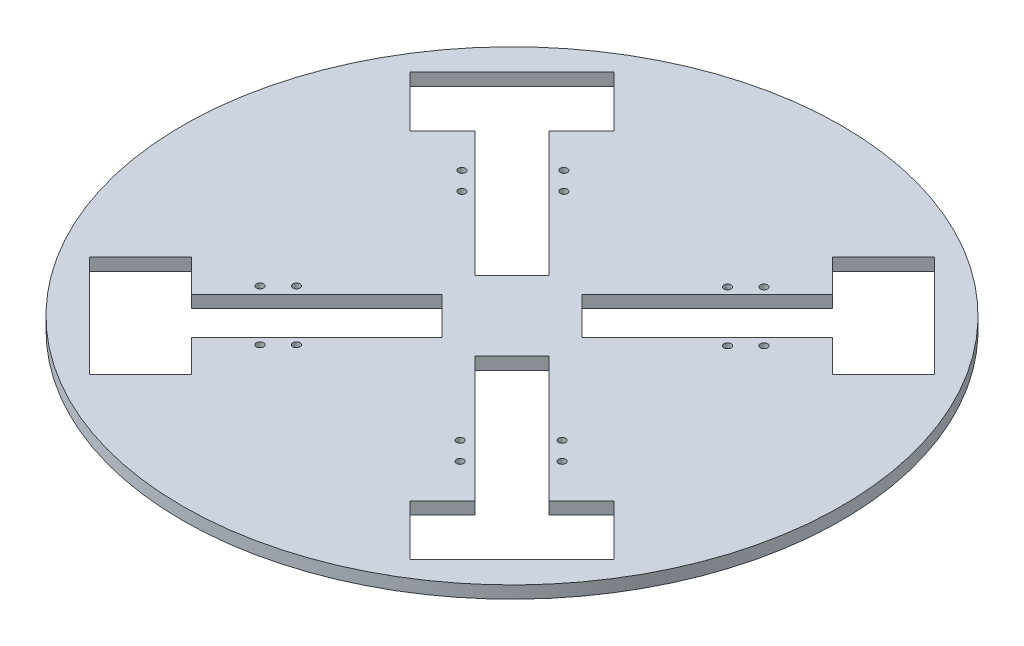
SolidWorks part; units mm, degrees
ref_plane "Front Plane" through (0, 0, 0) normal (0, 0, 1) x (1, 0, 0)
ref_plane "Top Plane" through (0, 0, 0) normal (0, 1, 0) x (1, 0, 0)
ref_plane "Right Plane" through (0, 0, 0) normal (1, 0, 0) x (0, 0, -1)
sketch "Sketch1" plane through (0, 0, 0) normal (0, 1, 0) x (1, 0, 0)
  line L1 (0, 0) -> (-200, 0) construction
  line L2 (0, 0) -> (0, 200) construction
  line L3 (0, 200) -> (-200, 200) construction
  line L4 (-200, 0) -> (-200, 200) construction
  circle A0 centre (-100, 100) radius 160
  point P8 (-100, 200)
  point P9 (-200, 100)
  dimension "D3" = 320
  dimension "D1" = 200
  dimension "D2" = 200
extrude "Boss-Extrude1" add sketch "Sketch1" along normal blind 6 contours A0
sketch "Sketch2" plane through (0, 6, 0) normal (0, 1, 0) x (1, 0, 0)
  line L0 (-260, 100) -> (60, 100) construction
  line L1 (-213.1371, -13.1371) -> (-100, 100) construction
  line L2 (-100, 100) -> (13.1371, 213.1371) construction
  line L3 (-213.1371, 213.1371) -> (13.1371, -13.1371) construction
  circle A0 centre (-100, 100) radius 160 construction
  dimension "D1" = 45
  dimension "D2" = 45
sketch "Sketch3" plane through (0, 0, 0) normal (0, -1, 0) x (1, 0, 0)
  line L0 (-22.2183, -227.2792) -> (-46.967, -202.5305)
  line L1 (-22.2183, -227.2792) -> (27.2792, -177.7817)
  line L2 (-46.967, -202.5305) -> (2.5305, -153.033)
  line L3 (27.2792, -177.7817) -> (2.5305, -153.033)
  line L4 (2.5305, -46.967) -> (27.2792, -22.2183)
  line L5 (2.5305, -46.967) -> (-46.967, 2.5305)
  line L6 (27.2792, -22.2183) -> (-22.2183, 27.2792)
  line L7 (-46.967, 2.5305) -> (-22.2183, 27.2792)
  line L8 (-153.033, 2.5305) -> (-177.7817, 27.2792)
  line L9 (-153.033, 2.5305) -> (-202.5305, -46.967)
  line L10 (-177.7817, 27.2792) -> (-227.2792, -22.2183)
  line L11 (-202.5305, -46.967) -> (-227.2792, -22.2183)
  line L12 (-177.7817, -227.2792) -> (-153.033, -202.5305)
  line L13 (-177.7817, -227.2792) -> (-227.2792, -177.7817)
  line L14 (-153.033, -202.5305) -> (-202.5305, -153.033)
  line L15 (-227.2792, -177.7817) -> (-202.5305, -153.033)
  line L16 (-213.1371, -213.1371) -> (13.1371, 13.1371) construction
  line L17 (-100, -100) -> (13.1371, -213.1371) construction
  line L18 (-213.1371, 13.1371) -> (-100, -100) construction
  point P26 (2.5305, -202.5305)
  point P27 (2.5305, 2.5305)
  point P28 (-202.5305, 2.5305)
  point P29 (-202.5305, -202.5305)
  dimension "D1" = 35
  dimension "D2" = 15
  dimension "D3" = 15
  dimension "D4" = 15
  dimension "D5" = 15
  dimension "D6" = 70
extrude "Cut-Extrude1" cut sketch "Sketch3" against normal through all
sketch "Sketch4" plane through (0, 0, 0) normal (0, -1, 0) x (1, 0, 0)
  line L0 (-13.2026, -31.2339) -> (-31.2339, -13.2026)
  line L1 (-13.2026, -31.2339) -> (-74.0138, -92.045)
  line L2 (-31.2339, -13.2026) -> (-92.045, -74.0138)
  line L3 (-74.0138, -92.045) -> (-92.045, -74.0138)
  line L4 (-168.7661, -13.2026) -> (-186.7974, -31.2339)
  line L5 (-168.7661, -13.2026) -> (-107.955, -74.0138)
  line L6 (-186.7974, -31.2339) -> (-125.9862, -92.045)
  line L7 (-107.955, -74.0138) -> (-125.9862, -92.045)
  line L8 (-202.5305, -46.967) -> (-153.033, 2.5305) construction
  line L9 (-186.7974, -168.7661) -> (-125.9862, -107.955)
  line L10 (-186.7974, -168.7661) -> (-168.7661, -186.7974)
  line L11 (-125.9862, -107.955) -> (-107.955, -125.9862)
  line L12 (-168.7661, -186.7974) -> (-107.955, -125.9862)
  line L13 (-13.2026, -168.7661) -> (-31.2339, -186.7974)
  line L14 (-13.2026, -168.7661) -> (-74.0138, -107.955)
  line L15 (-31.2339, -186.7974) -> (-92.045, -125.9862)
  line L16 (-74.0138, -107.955) -> (-92.045, -125.9862)
  line L17 (-100, -100) -> (13.1371, -213.1371) construction
  line L18 (-213.1371, -213.1371) -> (13.1371, 13.1371) construction
  line L19 (-213.1371, 13.1371) -> (-100, -100) construction
  line L20 (-46.967, 2.5305) -> (2.5305, -46.967) construction
  line L21 (-153.033, -202.5305) -> (-202.5305, -153.033) construction
  line L22 (2.5305, -153.033) -> (-46.967, -202.5305) construction
  point P22 (-83.0294, -116.9706)
  point P23 (-116.9706, -83.0294)
  point P26 (-83.0294, -83.0294)
  point P27 (-116.9706, -116.9706)
  point P35 (-100, -100)
  point P36 (-100, -100)
  line M20 (-202.5305, -153.033) -> (-153.033, -202.5305)
  line M22 (-153.033, 2.5305) -> (-202.5305, -46.967)
  line M26 (2.5305, -46.967) -> (-46.967, 2.5305)
  line M32 (-46.967, -202.5305) -> (2.5305, -153.033)
  dimension "D1" = 25.5
  dimension "D2" = 86
extrude "Cut-Extrude2" cut sketch "Sketch4" against normal through all contours L14 L16 L15 M32 | L12 L11 L9 M20 | L7 L5 L6 M22 | L3 L1 L2 M26
sketch "Sketch7" plane through (0, 0, 0) normal (0, -1, 0) x (1, 0, 0)
  line L0 (-153.033, -202.5305) -> (-168.7661, -186.7974) construction
  line L1 (-168.7661, -186.7974) -> (-107.955, -125.9862) construction
  line L2 (-153.033, -202.5305) -> (-168.7661, -186.7974) construction
  line L3 (-168.7661, -186.7974) -> (-107.955, -125.9862) construction
  circle A2 centre (-149.0025, -26.673) radius 1.75
  circle A10 centre (-148.5782, -173.7512) radius 1.75
  circle A20 centre (-140.1637, -35.5119) radius 1.75
  circle A21 centre (-164.9124, -60.2606) radius 1.75
  circle A22 centre (-173.7512, -51.4218) radius 1.75
  circle A25 centre (-173.327, -149.0025) radius 1.75
  circle A26 centre (-164.4881, -140.1637) radius 1.75
  circle A27 centre (-139.7394, -164.9124) radius 1.75
  circle A32 centre (-26.673, -50.9975) radius 1.75
  circle A33 centre (-35.5119, -59.8363) radius 1.75
  circle A34 centre (-60.2606, -35.0876) radius 1.75
  circle A35 centre (-51.4218, -26.2488) radius 1.75
  circle A36 centre (-50.9975, -173.327) radius 1.75
  circle A37 centre (-59.8363, -164.4881) radius 1.75
  circle A38 centre (-35.0876, -139.7394) radius 1.75
  circle A39 centre (-26.2488, -148.5782) radius 1.75
  point P29 (-100, -100)
  dimension "D9" = 3.5
  dimension "D1" = 12.5
  dimension "D2" = 35
  dimension "D3" = 35
  dimension "D4" = 12.5
  dimension "D5" = 37.1652
  dimension "D6" = 23.5
  dimension "D7" = 5.05
  dimension "D8" = 29.95
  dimension "D10" = 4
extrude "Cut-Extrude3" cut sketch "Sketch7" against normal through all
